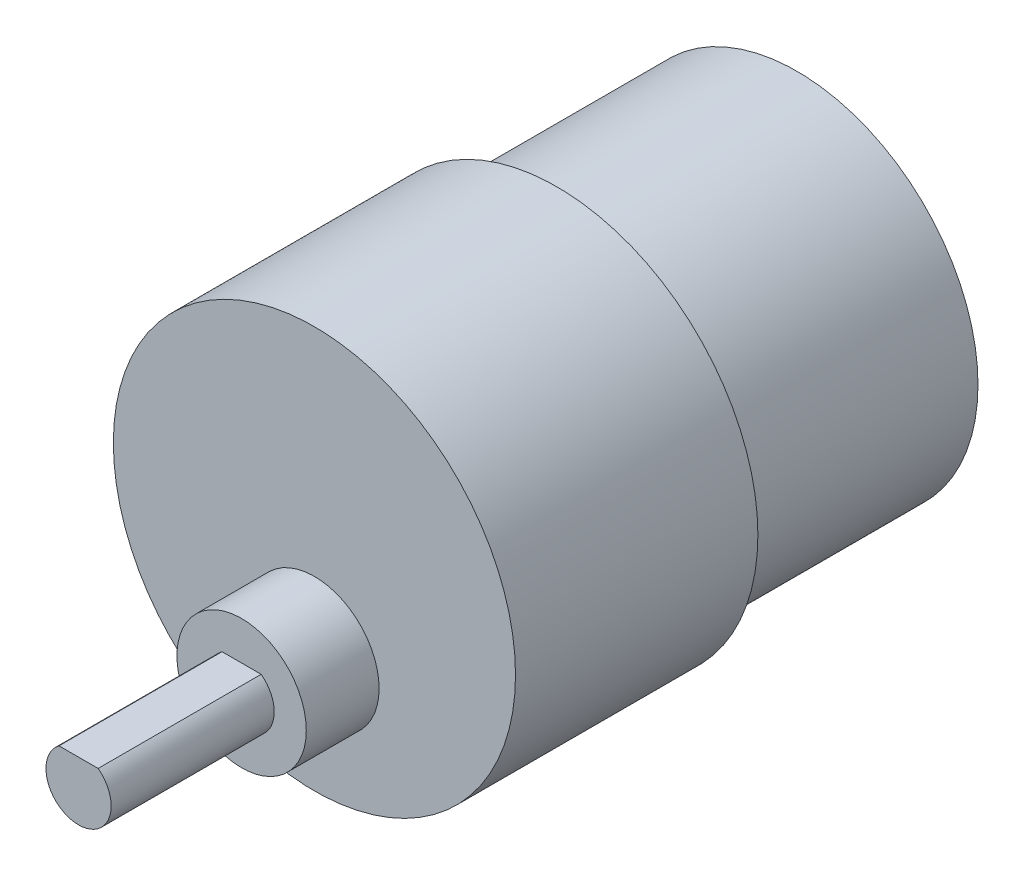
SolidWorks part; units mm, degrees
material "Aleación 6061"
ref_plane "Alzado" through (0, 0, 0) normal (0, 0, 1) x (1, 0, 0)
ref_plane "Planta" through (0, 0, 0) normal (0, 1, 0) x (1, 0, 0)
ref_plane "Vista lateral" through (0, 0, 0) normal (1, 0, 0) x (0, 0, -1)
sketch "Croquis1" plane through (0, 0, 0) normal (0, 0, 1) x (1, 0, 0)
  circle A0 centre (0, 0) radius 16.65
  dimension "D1" = 33.3
extrude "Saliente-Extruir1" add sketch "Croquis1" along normal blind 22.1
sketch "Croquis2" plane through (0, 0, 22.1) normal (0, 0, 1) x (1, 0, 0)
  circle A0 centre (0, 0) radius 18.5
  dimension "D1" = 37
extrude "Saliente-Extruir3" add sketch "Croquis2" along normal blind 22.3
sketch "Croquis3" plane through (0, 0, 44.4) normal (0, 0, 1) x (1, 0, 0)
  circle A1 centre (0, -7.35) radius 5.95
  dimension "D1" = 11.9
  dimension "D2" = 7.35
extrude "Saliente-Extruir4" add sketch "Croquis3" along normal blind 6.7
sketch "Croquis4" plane through (0, 0, 51.1) normal (0, 0, 1) x (1, 0, 0)
  line L1 (-1.8, -4.95) -> (1.8, -4.95)
  arc A0 (-1.8, -4.95) -> (1.8, -4.95) centre (0, -7.35) ccw
  point P1 (0, -4.95)
  point P3 (0, -10.35)
  dimension "D1" = 6
  dimension "D2" = 5.4
extrude "Saliente-Extruir5" add sketch "Croquis4" along normal blind 15
